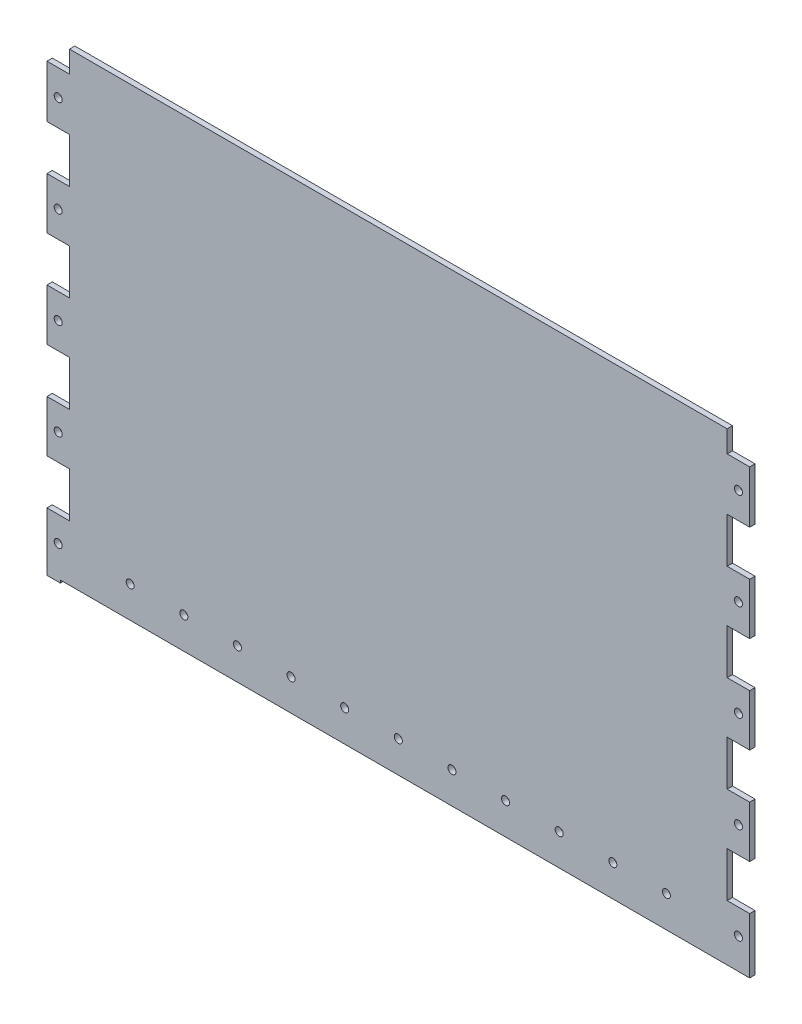
SolidWorks part; units mm, degrees
material "FR4"
ref_plane "前视基准面" through (0, 0, 0) normal (0, 0, 1) x (1, 0, 0)
ref_plane "上视基准面" through (0, 0, 0) normal (0, 1, 0) x (1, 0, 0)
ref_plane "右视基准面" through (0, 0, 0) normal (1, 0, 0) x (0, 0, -1)
sketch "草图1" plane through (0, 0, 0) normal (0, 0, 1) x (1, 0, 0)
  line L1 (131.05, -83.1) -> (-131.05, -83.1)
  line L2 (131.05, -83.1) -> (131.05, 83.1)
  line L3 (131.05, 83.1) -> (-131.05, 83.1)
  line L4 (-131.05, -83.1) -> (-131.05, 83.1)
  line L5 (131.05, -83.1) -> (-131.05, 83.1) construction
  line L6 (131.05, 83.1) -> (-131.05, -83.1) construction
  point P0 (0, 0)
  dimension "D1" = 262.1
  dimension "D2" = 166.2
extrude "凸台-拉伸1" add sketch "草图1" along normal mid plane 2
sketch "草图2" plane through (0, 0, 1) normal (0, 0, 1) x (1, 0, 0)
  line L5 (0, 0) -> (144.4976, 0) construction
  line L6 (0, 0) -> (0, 93.1697) construction
  line L20 (-131.05, 83.1) -> (-131.05, -83.1) construction
  line L21 (-131.05, 63.5) -> (-122.65, 63.5)
  line L23 (-131.05, 63.5) -> (-131.05, 46.7)
  line L28 (-131.05, 46.7) -> (-122.65, 46.7)
  line L29 (-122.65, 63.5) -> (-122.65, 46.7)
  line L30 (131.05, 83.1) -> (-131.05, 83.1) construction
  line L40 (-131.05, 27.5) -> (-122.65, 27.5)
  line L41 (-131.05, 27.5) -> (-131.05, 10.7)
  line L42 (-131.05, 10.7) -> (-122.65, 10.7)
  line L43 (-122.65, 27.5) -> (-122.65, 10.7)
  line L44 (-131.05, -8.5) -> (-122.65, -8.5)
  line L45 (-131.05, -8.5) -> (-131.05, -25.3)
  line L46 (-131.05, -25.3) -> (-122.65, -25.3)
  line L47 (-122.65, -8.5) -> (-122.65, -25.3)
  line L48 (-131.05, -44.5) -> (-122.65, -44.5)
  line L49 (-131.05, -44.5) -> (-131.05, -61.3)
  line L50 (-131.05, -61.3) -> (-122.65, -61.3)
  line L51 (-122.65, -44.5) -> (-122.65, -61.3)
  line L52 (-131.05, 63.5) -> (-131.05, 27.5) construction
  line L53 (131.05, 63.5) -> (131.05, 27.5) construction
  line L54 (122.65, -44.5) -> (122.65, -61.3)
  line L55 (131.05, -61.3) -> (122.65, -61.3)
  line L56 (131.05, -44.5) -> (131.05, -61.3)
  line L57 (131.05, -44.5) -> (122.65, -44.5)
  line L58 (122.65, -8.5) -> (122.65, -25.3)
  line L59 (131.05, -25.3) -> (122.65, -25.3)
  line L60 (131.05, -8.5) -> (131.05, -25.3)
  line L61 (131.05, -8.5) -> (122.65, -8.5)
  line L62 (122.65, 27.5) -> (122.65, 10.7)
  line L63 (131.05, 10.7) -> (122.65, 10.7)
  line L64 (131.05, 27.5) -> (131.05, 10.7)
  line L65 (131.05, 27.5) -> (122.65, 27.5)
  line L66 (122.65, 63.5) -> (122.65, 46.7)
  line L67 (131.05, 46.7) -> (122.65, 46.7)
  line L68 (131.05, 63.5) -> (131.05, 46.7)
  line L69 (131.05, 63.5) -> (122.65, 63.5)
  line L70 (-126.85, 83.1) -> (-126.85, 63.5) construction
  line L71 (-126.85, 73.3) -> (-126.85, 37.3) construction
  line L72 (131.05, 77.9891) -> (131.05, 86.2525) construction
  line L73 (-131.05, 83.1891) -> (131.05, 83.1891)
  line L74 (-131.05, 83.1891) -> (-131.05, 82.9891)
  line L75 (-131.05, 82.9891) -> (131.05, 82.9891)
  line L76 (131.05, 83.1891) -> (131.05, 82.9891)
  line L77 (131.05, -83.1) -> (131.05, 83.1) construction
  line L78 (-126.05, -83.1) -> (131.05, -83.1)
  line L79 (-126.05, -83.1) -> (-126.05, -82.1)
  line L80 (-126.05, -82.1) -> (131.05, -82.1)
  line L81 (131.05, -83.1) -> (131.05, -82.1)
  circle A0 centre (-126.85, 73.3) radius 1.5
  circle A1 centre (-126.85, 37.3) radius 1.5
  circle A2 centre (-126.85, 1.3) radius 1.5
  circle A3 centre (-126.85, -34.7) radius 1.5
  circle A4 centre (-126.85, -70.7) radius 1.5
  circle A5 centre (126.85, -70.7) radius 1.5
  circle A6 centre (126.85, -34.7) radius 1.5
  circle A7 centre (126.85, 1.3) radius 1.5
  circle A8 centre (126.85, 37.3) radius 1.5
  circle A9 centre (126.85, 73.3) radius 1.5
  dimension "D4" = 4
  dimension "D6" = 3
  dimension "D1" = 8.4
  dimension "D2" = 19.6
  dimension "D3" = 16.8
  dimension "D5" = 36
  dimension "D8" = 36
  dimension "D9" = 0.2
  dimension "D10" = 1
  dimension "D7" = 5
extrude "Cut-Extrude1" cut sketch "草图2" against normal blind 10
sketch "Sketch1" plane through (0, 0, 1) normal (0, 0, 1) x (1, 0, 0)
  circle A0 centre (100, -70.35) radius 1.5 construction
  circle A1 centre (80, -70.35) radius 1.5 construction
  circle A2 centre (60, -70.35) radius 1.5 construction
  circle A3 centre (40, -70.35) radius 1.5 construction
  circle A4 centre (20, -70.35) radius 1.5 construction
  circle A5 centre (0, -70.35) radius 1.5 construction
  circle A6 centre (-20, -70.35) radius 1.5 construction
  circle A7 centre (-40, -70.35) radius 1.5 construction
  circle A8 centre (-60, -70.35) radius 1.5 construction
  circle A9 centre (-80, -70.35) radius 1.5 construction
  circle A10 centre (-100, -70.35) radius 1.5 construction
  circle A11 centre (100, -70.35) radius 1.5
  circle A12 centre (80, -70.35) radius 1.5
  circle A13 centre (60, -70.35) radius 1.5
  circle A14 centre (40, -70.35) radius 1.5
  circle A15 centre (20, -70.35) radius 1.5
  circle A16 centre (0, -70.35) radius 1.5
  circle A17 centre (-20, -70.35) radius 1.5
  circle A18 centre (-40, -70.35) radius 1.5
  circle A19 centre (-60, -70.35) radius 1.5
  circle A20 centre (-80, -70.35) radius 1.5
  circle A21 centre (-100, -70.35) radius 1.5
extrude "Cut-Extrude2" cut sketch "Sketch1" against normal blind 10
sketch "Sketch2" plane through (0, 0, 1) normal (0, 0, 1) x (1, 0, 0)
  line L1 (-122.65, 82.9891) -> (122.65, 82.9891)
  line L2 (-122.65, 82.9891) -> (-122.65, 91.0891)
  line L3 (-122.65, 91.0891) -> (122.65, 91.0891)
  line L4 (122.65, 82.9891) -> (122.65, 91.0891)
  line L6 (123.05, 91.4891) -> (123.05, 83.1891) construction
  line L7 (-123.05, 91.4891) -> (-123.05, 83.1891) construction
  line L8 (135.24, 91.4891) -> (-131.05, 91.4891) construction
  line L9 (-131.05, 82.9891) -> (131.05, 82.9891) construction
  dimension "D1" = 0.4
  dimension "D2" = 0.4
  dimension "D3" = 0.4
extrude "Boss-Extrude1" add sketch "Sketch2" against normal blind 2
